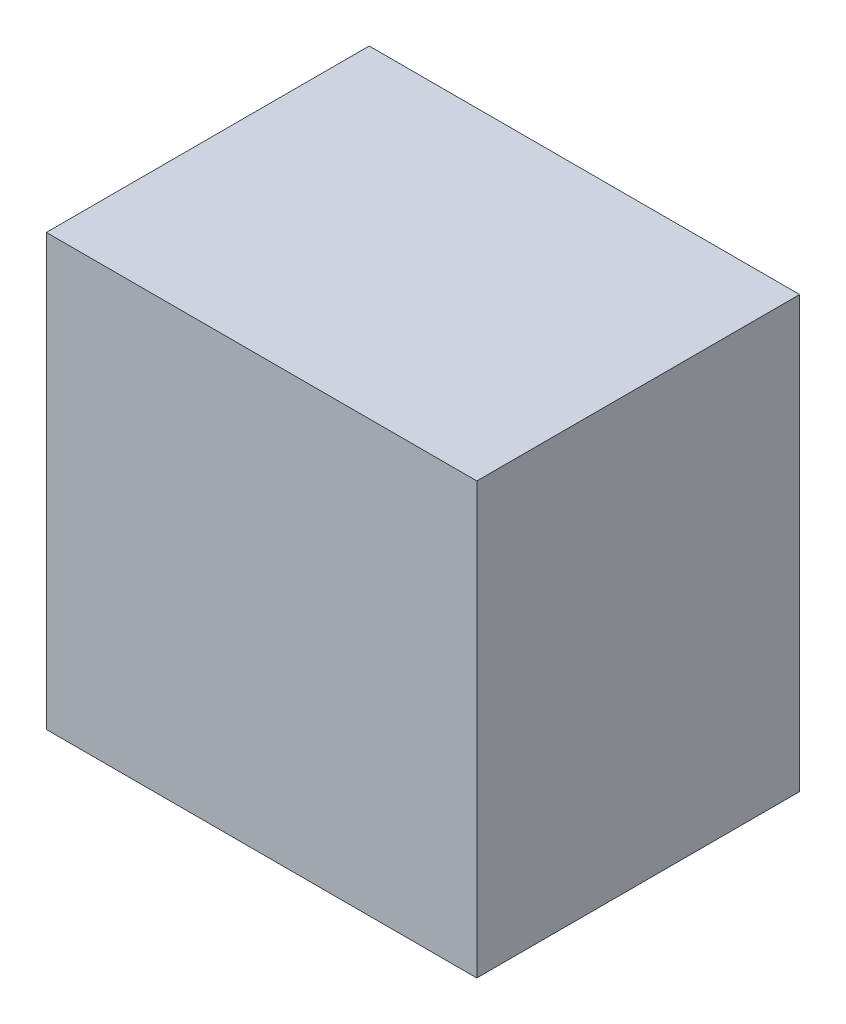
SolidWorks part; units mm, degrees
ref_plane "Front Plane" through (0, 0, 0) normal (0, 0, 1) x (1, 0, 0)
ref_plane "Top Plane" through (0, 0, 0) normal (0, 1, 0) x (1, 0, 0)
ref_plane "Right Plane" through (0, 0, 0) normal (1, 0, 0) x (0, 0, -1)
other "Configuration Table"
sketch "Sketch1" plane through (0, 0, 0) normal (0, 0, 1) x (1, 0, 0)
  line L1 (726, 1539) -> (742, 1539)
  line L2 (726, 1539) -> (726, 1555)
  line L3 (726, 1555) -> (742, 1555)
  line L4 (742, 1539) -> (742, 1555)
extrude "DET_MOTORLU_RAY_M12_soket_1" add sketch "Sketch1" against normal blind 12 from offset 740 separate body
